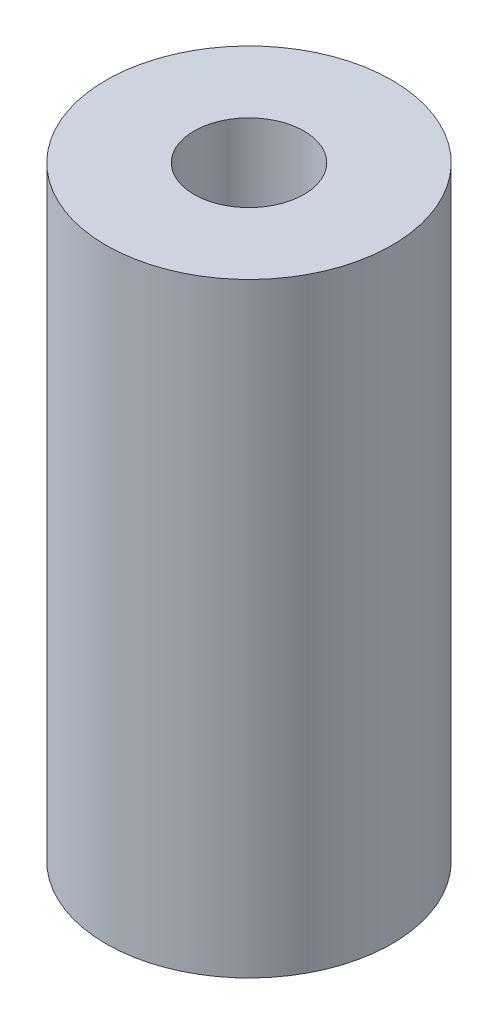
SolidWorks part; units mm, degrees
ref_plane "Спереди" through (0, 0, 0) normal (0, 0, 1) x (1, 0, 0)
ref_plane "Сверху" through (0, 0, 0) normal (0, 1, 0) x (1, 0, 0)
ref_plane "Справа" through (0, 0, 0) normal (1, 0, 0) x (0, 0, -1)
sketch "Эскиз1" plane through (0, 0, 0) normal (0, 1, 0) x (1, 0, 0)
  circle A0 centre (0, 0) radius 2.6
  circle A1 centre (0, 0) radius 1
  dimension "D1" = 5.2
  dimension "D2" = 2
extrude "Бобышка-Вытянуть1" add sketch "Эскиз1" along normal blind 11
